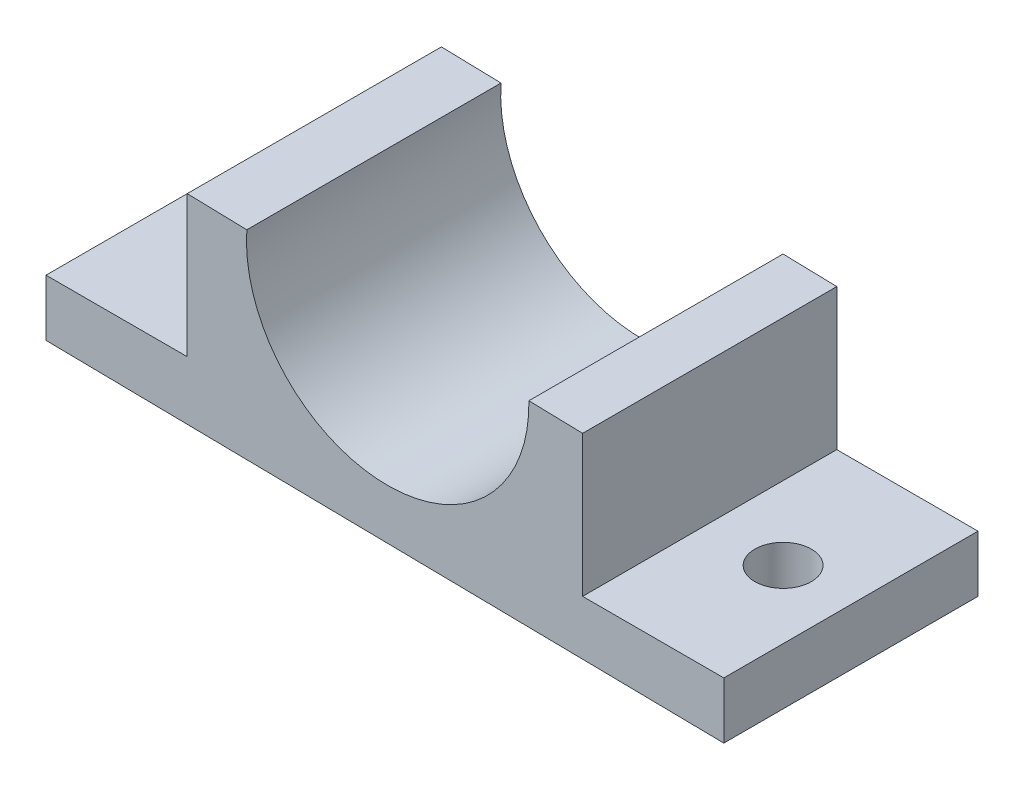
SolidWorks part; units mm, degrees
ref_plane "Front Plane" through (0, 0, 0) normal (0, 0, 1) x (1, 0, 0)
ref_plane "Top Plane" through (0, 0, 0) normal (0, 1, 0) x (1, 0, 0)
ref_plane "Right Plane" through (0, 0, 0) normal (1, 0, 0) x (0, 0, -1)
sketch "Sketch1" plane through (0, 0, 0) normal (0, 0, 1) x (1, 0, 0)
  line L0 (0, 0) -> (-152.4, 2.2186)
  line L1 (-152.4, 2.2186) -> (-152.4, 14.9186)
  line L2 (0, 0) -> (0, 12.7)
  line L3 (0, 12.7) -> (-31.75, 12.7)
  line L4 (-152.4, 14.9186) -> (-120.65, 14.9186)
  line L5 (-120.65, 14.9186) -> (-120.65, 46.6686)
  line L6 (-31.75, 12.7) -> (-31.75, 44.45)
  line L8 (-120.65, 46.6686) -> (-31.75, 44.45)
  circle A0 centre (-75.5737, 44.1312) radius 31.75
  dimension "D1" = 12.7
  dimension "D2" = 31.75
  dimension "D3" = 44.45
  dimension "D4" = 152.4
extrude "Boss-Extrude2" add sketch "Sketch1" along normal blind 57.15 contours A0 L8 L5 L4 L1 L0 L2 L3 L6
sketch "Sketch6" plane through (0, 12.7, 0) normal (0, 1, 0) x (1, 0, 0)
  line L0 (-107.3237, -57.15) -> (-43.8237, -57.15) construction
  line L1 (-152.4, -57.15) -> (-120.65, -57.15) construction
  line L2 (0, -57.15) -> (-31.75, -57.15) construction
  line L3 (-75.5737, -57.15) -> (-75.5737, -70.3443)
  circle A0 centre (-15.2487, -28.575) radius 6.35
  circle A1 centre (-135.8987, -28.575) radius 6.35
  dimension "D1" = 120.65
  dimension "D2" = 28.575
  dimension "D3" = 28.575
  dimension "D4" = 60.325
sketch "Sketch8" plane through (0, 14.9186, 0) normal (0, 1, 0) x (1, 0, 0)
  line L1 (-152.4, -57.15) -> (-120.65, -57.15) construction
  line L2 (-75.5737, -57.15) -> (-75.5737, -70.3443) construction
  circle A0 centre (-135.8987, -28.575) radius 6.35
  dimension "D1" = 28.575
  dimension "D2" = 60.325
extrude "Cut-Extrude8" cut sketch "Sketch8" against normal blind 91.948
extrude "Cut-Extrude9" cut sketch "Sketch6" against normal blind 91.948 contours A0
